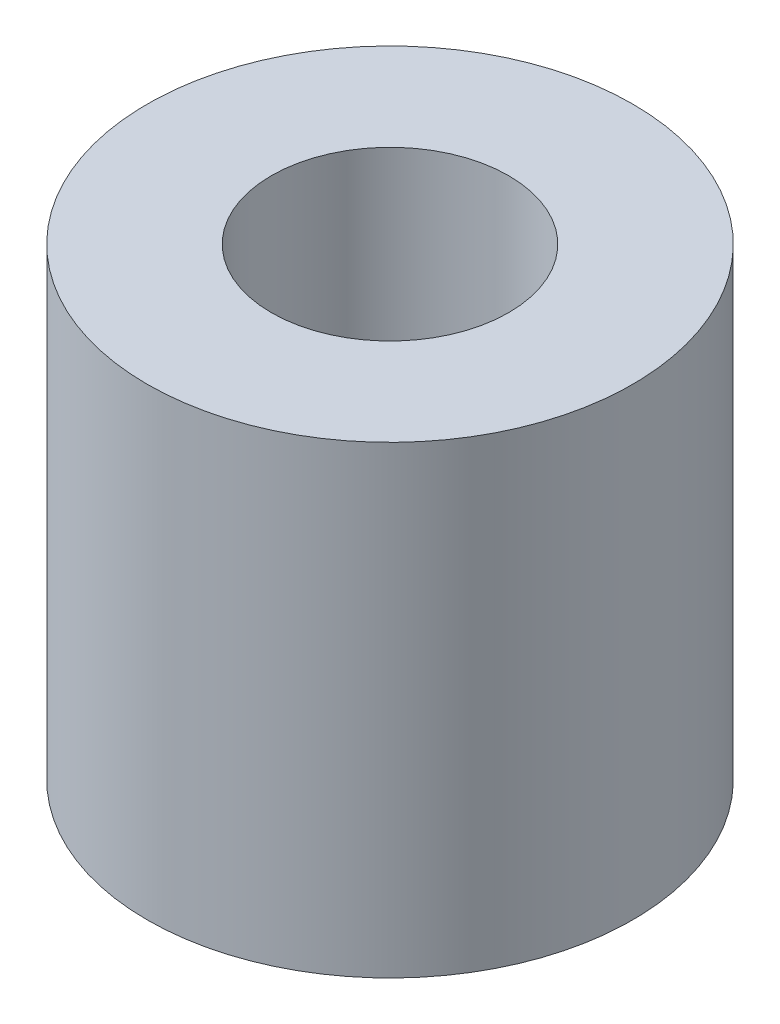
SolidWorks part; units mm, degrees
ref_plane "Front Plane" through (0, 0, 0) normal (0, 0, 1) x (1, 0, 0)
ref_plane "Top Plane" through (0, 0, 0) normal (0, 1, 0) x (1, 0, 0)
ref_plane "Right Plane" through (0, 0, 0) normal (1, 0, 0) x (0, 0, -1)
sketch "Sketch1" plane through (0, 0, 0) normal (0, 1, 0) x (1, 0, 0)
  circle A0 centre (0, 0) radius 2.25
  circle A2 centre (0, 0) radius 1.1
extrude "Boss-Extrude1" add sketch "Sketch1" along normal blind 4.3
